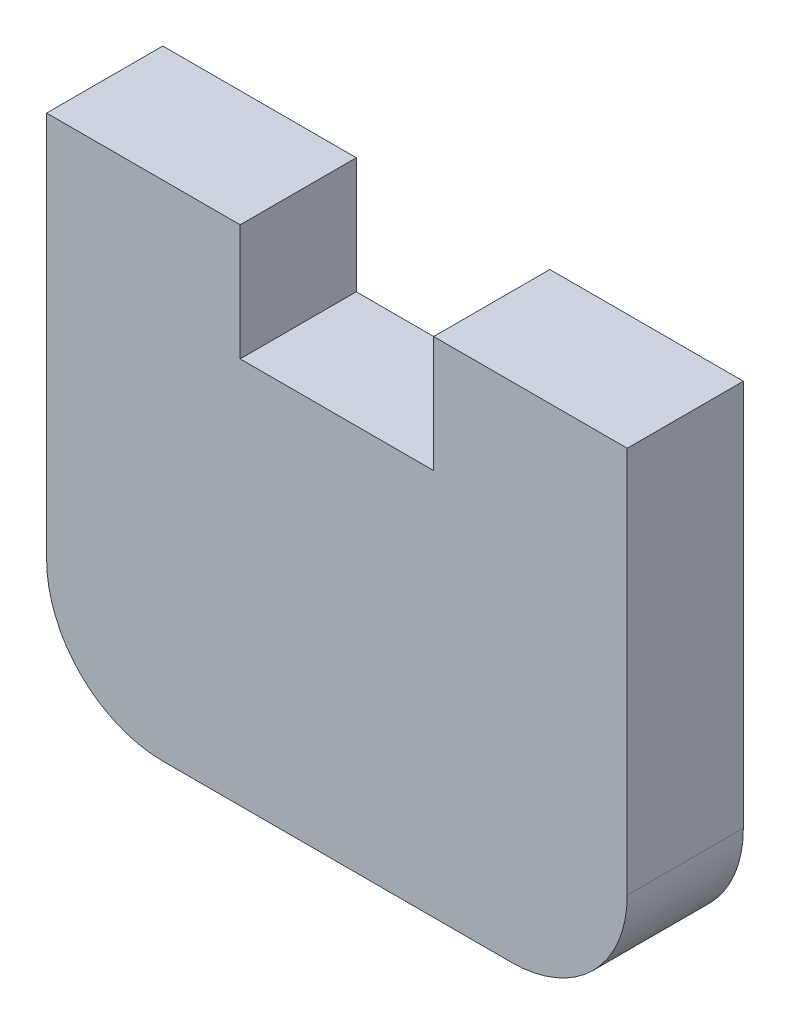
SolidWorks part; units mm, degrees
ref_plane "Alzado" through (0, 0, 0) normal (0, 0, 1) x (1, 0, 0)
ref_plane "Planta" through (0, 0, 0) normal (0, 1, 0) x (1, 0, 0)
ref_plane "Vista lateral" through (0, 0, 0) normal (1, 0, 0) x (0, 0, -1)
sketch "Croquis1" plane through (0, 0, 0) normal (0, 0, 1) x (1, 0, 0)
  line L0 (0, 22.001) -> (-5, 22.001)
  line L1 (-5, 22.001) -> (-5, 12.001)
  line L2 (10, 19.001) -> (10, 22.001)
  line L3 (10, 19.001) -> (10, 12.001)
  line L4 (10, 22.001) -> (5, 22.001)
  line L5 (5, 22.001) -> (5, 19.001)
  line L6 (5, 19.001) -> (0, 19.001)
  line L12 (0, 19.001) -> (0, 22.001)
  line L13 (7, 9.001) -> (-2, 9.001)
  arc A0 (-5, 12.001) -> (-2, 9.001) centre (-2, 12.001) ccw
  arc A1 (10, 12.001) -> (7, 9.001) centre (7, 12.001) cw
  dimension "D1" = 3
extrude "Saliente-Extruir1" add sketch "Croquis1" along normal blind 3
